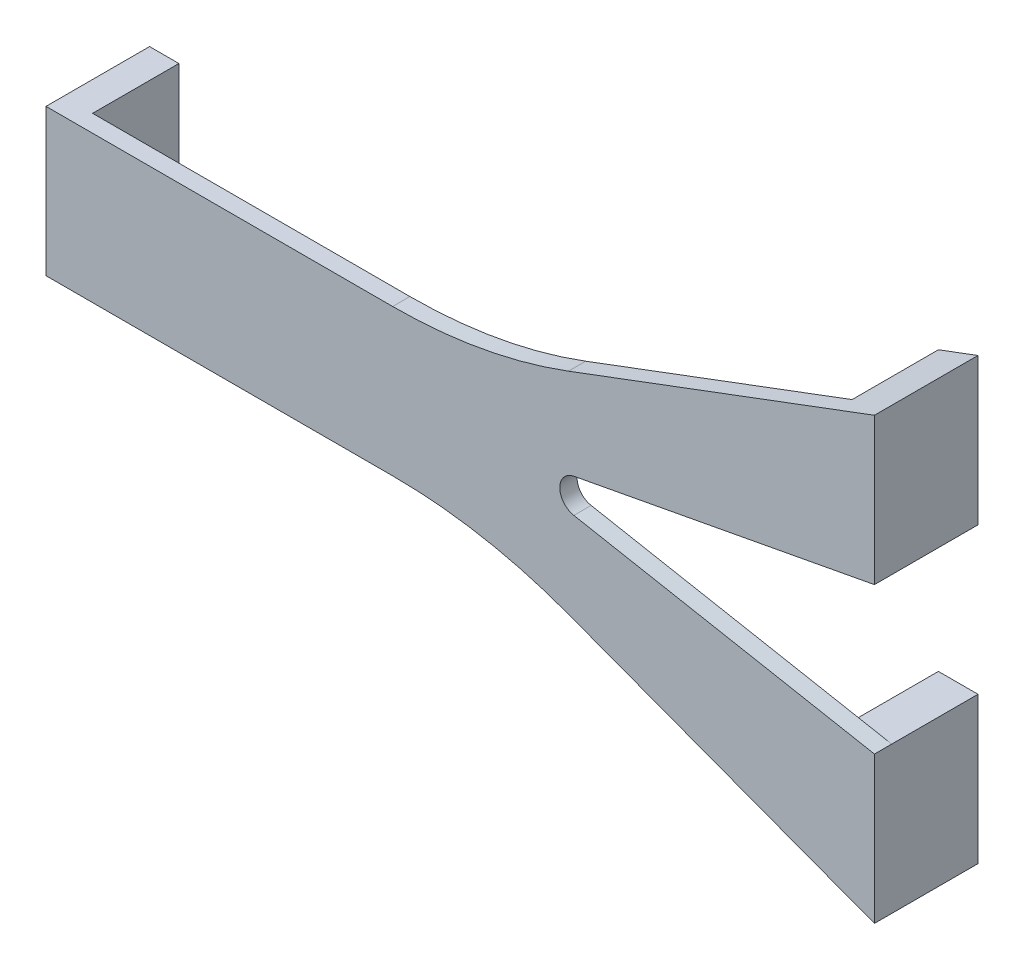
SolidWorks part; units mm, degrees
ref_plane "정면" through (0, 0, 0) normal (0, 0, 1) x (1, 0, 0)
ref_plane "윗면" through (0, 0, 0) normal (0, 1, 0) x (1, 0, 0)
ref_plane "우측면" through (0, 0, 0) normal (1, 0, 0) x (0, 0, -1)
sketch "스케치1" plane through (0, 0, 0) normal (0, 0, 1) x (1, 0, 0)
  line L0 (-0.5189, 12.1964) -> (34.9388, 25.5)
  line L1 (-61.0612, 8.5) -> (-20.8934, 8.5)
  line L2 (-61.0612, 8.5) -> (-61.0612, -8.5)
  line L5 (0.1075, 1.9657) -> (34.9388, 8.5)
  line L6 (34.9388, 8.5) -> (34.9388, 25.5)
  line L7 (-61.0612, -8.5) -> (-20.8934, -8.5)
  line L8 (0.1075, -1.9657) -> (34.9388, -8.5)
  line L9 (34.9388, -8.5) -> (34.9388, -25.5)
  line L10 (-0.5189, -12.1964) -> (34.9388, -25.5)
  line L11 (55, 0) -> (-55, 0) construction
  arc A0 (0.1075, -1.9657) -> (0.1075, 1.9657) centre (0.4762, 0) cw
  arc A1 (-20.8934, -8.5) -> (-0.5189, -12.1964) centre (-20.8934, -66.5) cw
  arc A2 (-20.8934, 8.5) -> (-0.5189, 12.1964) centre (-20.8934, 66.5) ccw
  dimension "D1" = 2
  dimension "D4" = 58
  dimension "D2" = 96
  dimension "D3" = 17
extrude "보스-돌출1" add sketch "스케치1" along normal blind 2 contours L7 A1 L10 L9 L8 A0 L5 L6 L0 A2 L1 L2
sketch "스케치3" plane through (0, 0, 0) normal (0, 0, -1) x (-1, 0, 0)
  line L0 (61.0612, 8.5) -> (20.8934, 8.5) construction
  line L1 (61.0612, -8.5) -> (57.6612, -8.5)
  line L2 (61.0612, -8.5) -> (61.0612, 8.5)
  line L3 (61.0612, 8.5) -> (57.6612, 8.5)
  line L4 (57.6612, -8.5) -> (57.6612, 8.5)
  line L5 (55, 0) -> (-55, 0) construction
  line L6 (-34.9388, -25.5) -> (-30.3488, -25.5)
  line L7 (-34.9388, -25.5) -> (-34.9388, -8.5)
  line L8 (-34.9388, -8.5) -> (-30.3488, -8.5)
  line L9 (-30.3488, -25.5) -> (-30.3488, -8.5)
  line L10 (-34.9388, 8.5) -> (-30.3488, 8.5)
  line L11 (-30.3488, 25.5) -> (-30.3488, 8.5)
  line L12 (-34.9388, 25.5) -> (-30.3488, 25.5)
  line L13 (-34.9388, 25.5) -> (-34.9388, 8.5)
  point P12 (-34.9388, -8.5)
  line M7 (0.5189, 12.1964) -> (-34.9388, 25.5)
  line M8 (-34.9388, 25.5) -> (-34.9388, 8.5)
  line M11 (-34.9388, -8.5) -> (-34.9388, -25.5)
  line M12 (-34.9388, -25.5) -> (0.5189, -12.1964)
  dimension "D1" = 4.59
  dimension "D2" = 3.4
extrude "보스-돌출2" add sketch "스케치3" along normal blind 10 contours L11 L10 M7 M8 | L9 L8 M12 M11 | L4 L3 L2 L1
